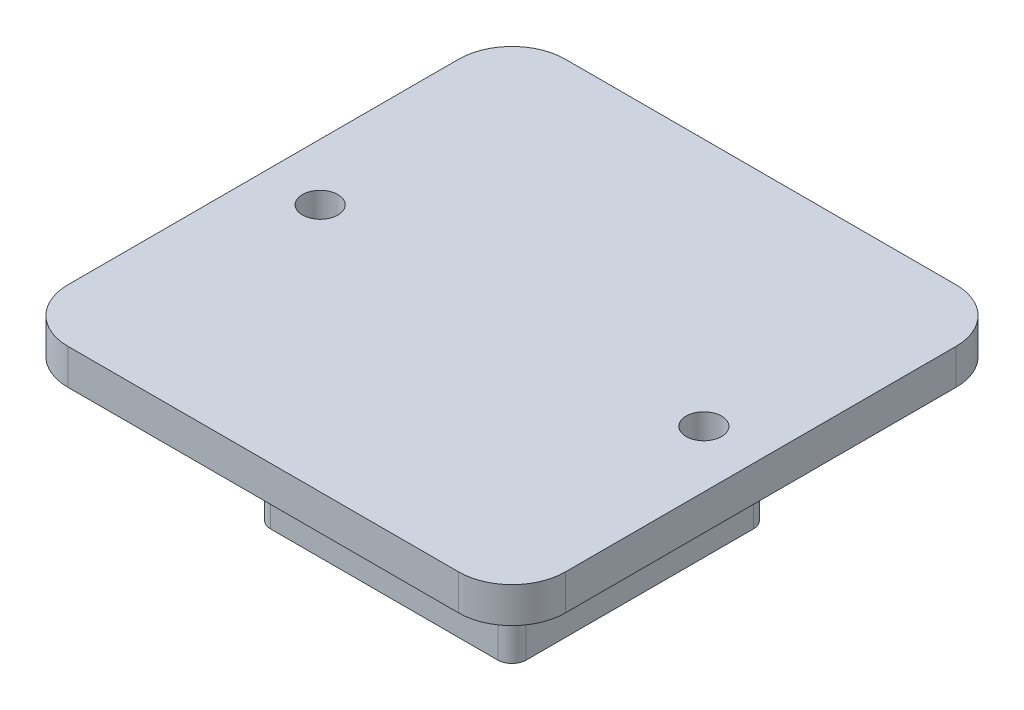
SolidWorks part; units mm, degrees
ref_plane "Front Plane" through (0, 0, 0) normal (0, 0, 1) x (1, 0, 0)
ref_plane "Top Plane" through (0, 0, 0) normal (0, 1, 0) x (1, 0, 0)
ref_plane "Right Plane" through (0, 0, 0) normal (1, 0, 0) x (0, 0, -1)
sketch "Sketch1" plane through (0, 0, 0) normal (0, 1, 0) x (1, 0, 0)
  line L1 (-15.01, -15.01) -> (15.01, -15.01)
  line L2 (-15.01, -15.01) -> (-15.01, 15.01)
  line L3 (-15.01, 15.01) -> (15.01, 15.01)
  line L4 (15.01, -15.01) -> (15.01, 15.01)
  line L5 (-15.01, -15.01) -> (15.01, 15.01) construction
  line L6 (-15.01, 15.01) -> (15.01, -15.01) construction
  line L7 (-18, -18) -> (18, -18)
  line L8 (-18, -18) -> (-18, 18)
  line L9 (-18, 18) -> (18, 18)
  line L10 (18, -18) -> (18, 18)
  line L11 (-18, -18) -> (18, 18) construction
  line L12 (-18, 18) -> (18, -18) construction
  point P0 (0, 0)
  point P6 (0, 0)
  dimension "D1" = 30.02
  dimension "D2" = 30.02
  dimension "D3" = 36
  dimension "D4" = 36
extrude "Boss-Extrude1" add sketch "Sketch1" along normal blind 20
sketch "Sketch2" plane through (0, 20, 0) normal (0, 1, 0) x (1, 0, 0)
  line L1 (-35, -35) -> (35, -35)
  line L2 (-35, -35) -> (-35, 35)
  line L3 (-35, 35) -> (35, 35)
  line L4 (35, -35) -> (35, 35)
  line L5 (-35, -35) -> (35, 35) construction
  line L6 (-35, 35) -> (35, -35) construction
  point P0 (0, 0)
  dimension "D1" = 70
  dimension "D2" = 70
extrude "Boss-Extrude2" add sketch "Sketch2" along normal blind 5
fillet "Fillet1" radius 7.5 4 edges at (35, 22.5, -35) (35, 22.5, 35) (-35, 22.5, 35) (-35, 22.5, -35)
sketch "Sketch3" plane through (0, 25, 0) normal (0, 1, 0) x (1, 0, 0)
  line L0 (-27, 0) -> (27, 0) construction
  circle A0 centre (-27, 0) radius 2.5
  circle A1 centre (27, 0) radius 2.5
  point P4 (0, 0)
  dimension "D2" = 5
  dimension "D3" = 5
  dimension "D1" = 54
extrude "Cut-Extrude1" cut sketch "Sketch3" against normal through all
fillet "Fillet2" radius 2 4 edges at (18, 10, -18) (18, 10, 18) (-18, 10, -18) (-18, 10, 18)
fillet "Fillet3" radius 5 8 edges at (-17.4142, 20, 17.4142) (-18, 20, 0) (-17.4142, 20, -17.4142) (0, 20, -18) (17.4142, 20, -17.4142) (18, 20, 0) (17.4142, 20, 17.4142) (0, 20, 18)
